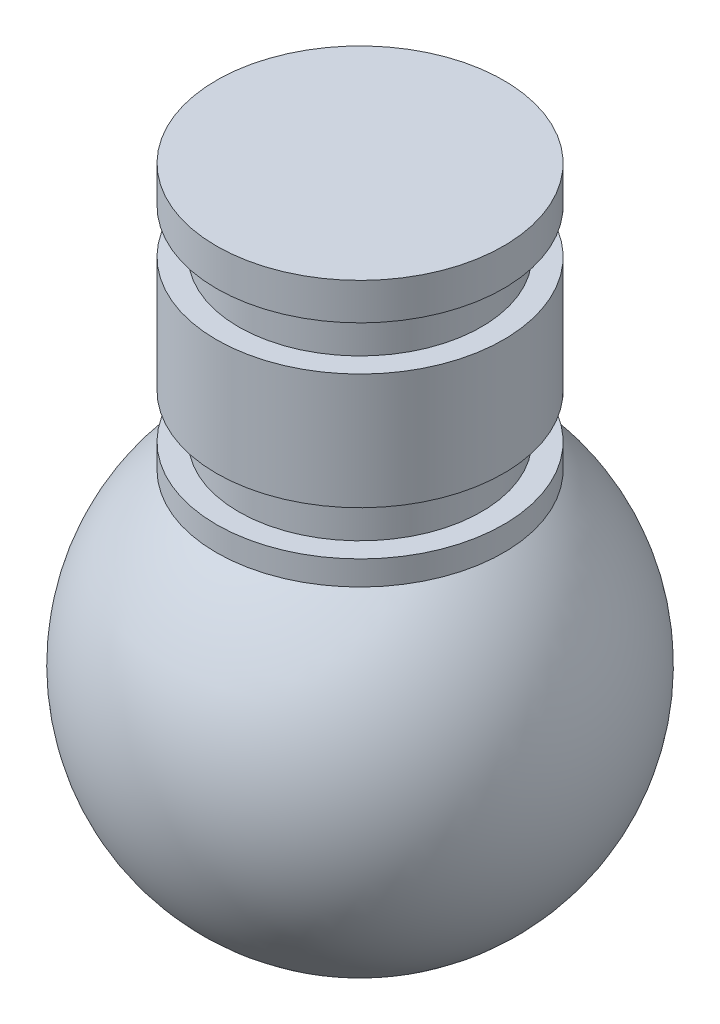
SolidWorks part; units mm, degrees
ref_plane "Front Plane" through (0, 0, 0) normal (0, 0, 1) x (1, 0, 0)
ref_plane "Top Plane" through (0, 0, 0) normal (0, 1, 0) x (1, 0, 0)
ref_plane "Right Plane" through (0, 0, 0) normal (1, 0, 0) x (0, 0, -1)
sketch "Sketch1" plane through (0, 0, 0) normal (0, 0, 1) x (1, 0, 0)
  line L4 (6640.0846, 3596.9612) -> (6640.0846, 3502.9812)
  line L5 (6619.5106, 3596.9612) -> (6619.5106, 3591.6888)
  line L6 (6619.5106, 3585.3388) -> (6619.5106, 3568.7501)
  line L7 (6619.5106, 3562.4001) -> (6619.5106, 3558.9133)
  line L8 (6622.6856, 3591.6888) -> (6622.6856, 3585.3388)
  line L9 (6622.6856, 3568.7501) -> (6622.6856, 3562.4001)
  line L10 (6640.0846, 3596.9612) -> (6619.5106, 3596.9612)
  line L11 (6622.6856, 3591.6888) -> (6619.5106, 3591.6888)
  line L12 (6622.6856, 3585.3388) -> (6619.5106, 3585.3388)
  line L13 (6619.5106, 3562.4001) -> (6622.6856, 3562.4001)
  line L14 (6619.5106, 3568.7501) -> (6622.6856, 3568.7501)
  arc A2 (6619.5106, 3558.9133) -> (6640.0846, 3502.9812) centre (6640.0846, 3534.7312) ccw
  point P6 (0, 0.001)
  point P7 (0.001, 0.001)
  point P8 (0.001, 0)
  point P14 (0, 0.001)
  point P15 (0.001, 0.001)
  point P16 (0.001, 0)
revolve "Revolve1" add sketch "Sketch1" angle 360 about L4
